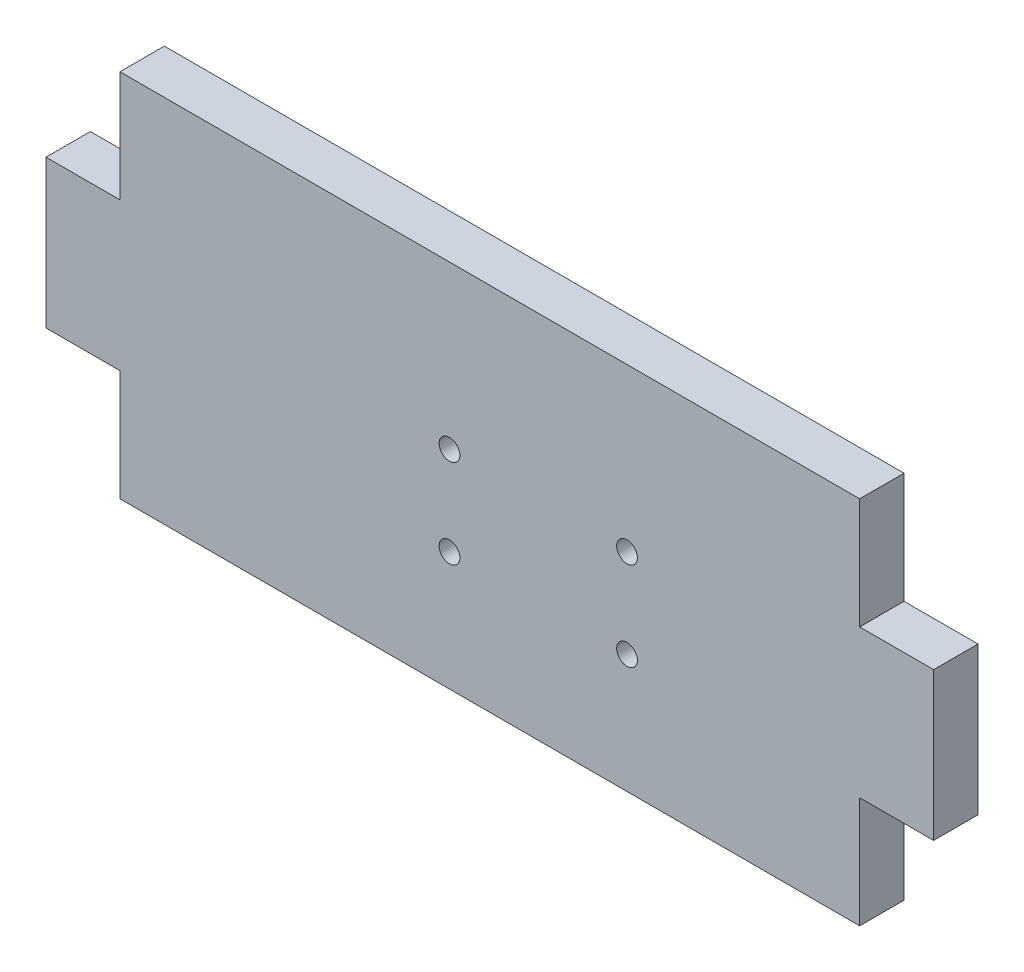
SolidWorks part; units mm, degrees
ref_plane "Plan de face" through (0, 0, 0) normal (0, 0, 1) x (1, 0, 0)
ref_plane "Plan de dessus" through (0, 0, 0) normal (0, 1, 0) x (1, 0, 0)
ref_plane "Plan de droite" through (0, 0, 0) normal (1, 0, 0) x (0, 0, -1)
sketch "Esquisse1" plane through (0, 0, 0) normal (0, 0, 1) x (1, 0, 0)
  line L1 (0, 0) -> (100, 0)
  line L2 (0, 0) -> (0, 50)
  line L3 (0, 50) -> (100, 50)
  line L4 (100, 0) -> (100, 50)
  line L5 (0, 35) -> (-10, 35)
  line L6 (0, 35) -> (0, 15)
  line L7 (0, 15) -> (-10, 15)
  line L8 (-10, 35) -> (-10, 15)
  line L9 (100, 35) -> (110, 35)
  line L10 (100, 35) -> (100, 15)
  line L11 (100, 15) -> (110, 15)
  line L12 (110, 35) -> (110, 15)
  point P13 (-10, 25)
  point P14 (0, 25)
  point P15 (110, 25)
  point P16 (100, 25)
  dimension "D1" = 100
  dimension "D2" = 50
  dimension "D3" = 10
  dimension "D4" = 20
  dimension "D5" = 10
  dimension "D6" = 20
extrude "Boss.-Extru.1" add sketch "Esquisse1" along normal blind 6 contours L5 L8 L7 L2 | L1 L4 L3 L2 | L12 L9 L4 L11
sketch "Esquisse2" plane through (0, 0, 0) normal (0, 0, -1) x (-1, 0, 0)
  circle A0 centre (-44.5503, 16.0653) radius 1.4
  circle A1 centre (-44.5503, 28.0653) radius 1.4
  circle A2 centre (-68.5503, 28.0653) radius 1.4
  circle A3 centre (-68.5503, 16.0653) radius 1.4
  dimension "D1" = 2.8
  dimension "D2" = 2.8
  dimension "D3" = 2.8
  dimension "D4" = 2.8
extrude "Enlèv. mat.-Extru.1" cut sketch "Esquisse2" against normal up to surface (6 mm away) up to face at (50, 25, 6)
sketch "Esquisse3" plane through (0, 0, 0) normal (0, 0, -1) x (-1, 0, 0)
  circle A0 centre (-68.5503, 28.0653) radius 3
  circle A1 centre (-44.5503, 28.0653) radius 3
  circle A2 centre (-44.5503, 16.0653) radius 3
  circle A3 centre (-68.5503, 16.0653) radius 3
  dimension "D1" = 6
extrude "Enlèv. mat.-Extru.2" cut sketch "Esquisse3" against normal blind 4
